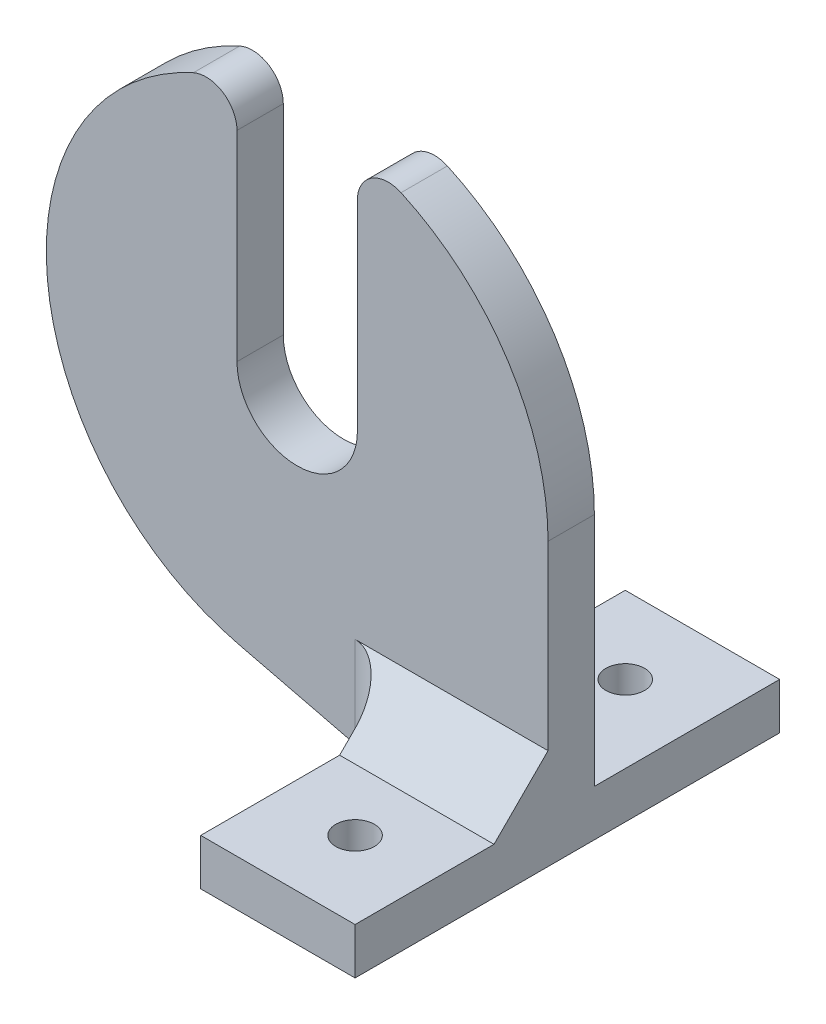
SolidWorks part; units mm, degrees
ref_plane "Front Plane" through (0, 0, 0) normal (0, 0, 1) x (1, 0, 0)
ref_plane "Top Plane" through (0, 0, 0) normal (0, 1, 0) x (1, 0, 0)
ref_plane "Right Plane" through (0, 0, 0) normal (1, 0, 0) x (0, 0, -1)
sketch "Sketch1" plane through (0, 0, 0) normal (0, 0, 1) x (1, 0, 0)
  line L0 (41.275, -41.275) -> (0, -41.275)
  line L1 (41.275, 0) -> (41.275, -41.275)
  line L2 (-9.906, 0) -> (-9.906, 40.0687)
  line L3 (9.906, 0) -> (9.906, 40.0687)
  circle A0 centre (0, 0) radius 9.906 construction
  arc A1 (41.275, 0) -> (9.906, 40.0687) centre (0, 0) ccw
  arc A2 (-9.906, 40.0687) -> (0, -41.275) centre (0, 0) ccw
  arc A3 (9.906, 0) -> (-9.906, 0) centre (0, 0) cw
  circle A4 centre (0, 0) radius 38.1 construction
  dimension "D1" = 19.812
  dimension "D2" = 82.55
  dimension "D3" = 76.2
  dimension "D4" = 3.175
extrude "Boss-Extrude1" add sketch "Sketch1" along normal blind 7.62
sketch "Sketch2" plane through (0, 0, 7.62) normal (0, 0, 1) x (1, 0, 0)
  line L0 (41.275, -41.275) -> (41.275, 0) construction
  line L5 (41.275, -38.735) -> (15.875, -38.735)
  line L6 (41.275, -38.735) -> (41.275, -46.355)
  line L7 (41.275, -46.355) -> (15.875, -46.355)
  line L8 (15.875, -38.735) -> (15.875, -46.355)
  line L9 (0, -41.275) -> (41.275, -41.275) construction
  dimension "D1" = 25.4
  dimension "D2" = 2.54
  dimension "D3" = 5.08
extrude "Boss-Extrude2" add sketch "Sketch2" along normal blind 31.75 and the other way blind 38.1
sketch "Sketch3" plane through (0, 0, 7.62) normal (0, 0, 1) x (1, 0, 0)
  line L0 (15.875, -46.355) -> (-9.7776, -40.1002)
  line L1 (15.875, -41.275) -> (15.875, -46.355)
  line L7 (0, -41.275) -> (15.875, -41.275)
  line L8 (15.875, -41.275) -> (15.875, -38.735)
  line L9 (15.875, -38.735) -> (41.275, -38.735)
  line L10 (41.275, -38.735) -> (41.275, 0)
  line L11 (9.906, 40.0687) -> (9.906, 0)
  line L12 (-9.906, 0) -> (-9.906, 40.0687)
  line L13 (0, -41.275) -> (15.875, -41.275)
  arc A0 (-9.906, 40.0687) -> (0, -41.275) centre (0, 0) ccw construction
  arc A4 (41.275, 0) -> (9.906, 40.0687) centre (0, 0) ccw
  arc A5 (-9.906, 0) -> (9.906, 0) centre (0, 0) ccw
  arc A6 (-9.906, 40.0687) -> (0, -41.275) centre (0, 0) ccw
  arc A9 (-9.7776, -40.1002) -> (0, -41.275) centre (0, 0) ccw
  dimension "D1" = 0
extrude "Boss-Extrude3" add sketch "Sketch3" against normal blind 7.62
sketch "Sketch4" plane through (0, -38.735, 0) normal (0, 1, 0) x (1, 0, 0)
  line L0 (41.275, -39.37) -> (15.875, -39.37) construction
  line L1 (15.875, -7.62) -> (15.875, -39.37) construction
  line L2 (15.875, 30.48) -> (15.875, 0) construction
  line L3 (41.275, 30.48) -> (15.875, 30.48) construction
  circle A0 centre (28.575, -26.67) radius 3.175
  circle A1 centre (28.575, 17.78) radius 3.175
  dimension "D1" = 6.35
  dimension "D4" = 6.35
  dimension "D2" = 12.7
  dimension "D3" = 12.7
  dimension "D5" = 12.7
  dimension "D6" = 12.7
extrude "Cut-Extrude1" cut sketch "Sketch4" against normal blind 7.62
chamfer "Chamfer1" distance 8.89 angle 45 1 edges at (28.575, -38.735, 7.62)
fillet "Fillet1" radius 6.35 2 edges at (15.875, -38.1, 7.62) (15.875, -42.545, 0)
fillet "Fillet2" radius 5.08 2 edges at (9.906, 40.0687, 3.81) (-9.906, 40.0687, 3.81)
sketch "Sketch5" plane through (0, 0, 0) normal (0, 0, -1) x (-1, 0, 0)
  circle A0 centre (0, 0) radius 37.5
  dimension "D1" = 75
